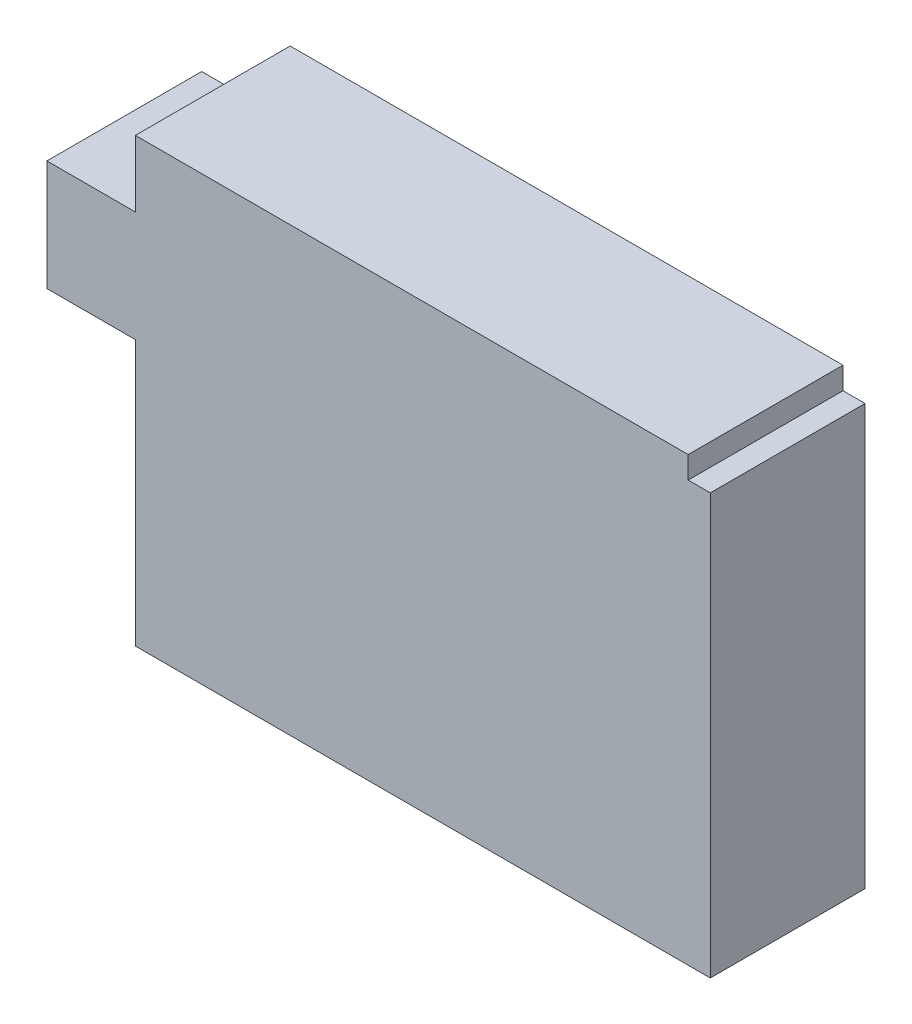
SolidWorks part; units mm, degrees
ref_plane "Alzado" through (0, 0, 0) normal (0, 0, 1) x (1, 0, 0)
ref_plane "Planta" through (0, 0, 0) normal (0, 1, 0) x (1, 0, 0)
ref_plane "Vista lateral" through (0, 0, 0) normal (1, 0, 0) x (0, 0, -1)
sketch "Croquis1" plane through (0, 0, 0) normal (0, 0, 1) x (1, 0, 0)
  line L0 (0, 0) -> (0, 12)
  line L1 (0, 12) -> (-4, 12)
  line L2 (-4, 12) -> (-4, 17)
  line L4 (25, 20) -> (25, 19)
  line L5 (25, 19) -> (26, 19)
  line L6 (26, 19) -> (26, 0)
  line L7 (26, 0) -> (0, 0)
  line L8 (-4, 17) -> (0, 17)
  line L9 (0, 17) -> (0, 20)
  line L10 (0, 20) -> (25, 20)
  line L11 (0, 12) -> (0, 17) construction
  dimension "D1" = 4
  dimension "D2" = 5
  dimension "D3" = 19
  dimension "D4" = 12
  dimension "D5" = 20
  dimension "D6" = 26
  dimension "D7" = 1
extrude "Saliente-Extruir1" add sketch "Croquis1" along normal blind 7
